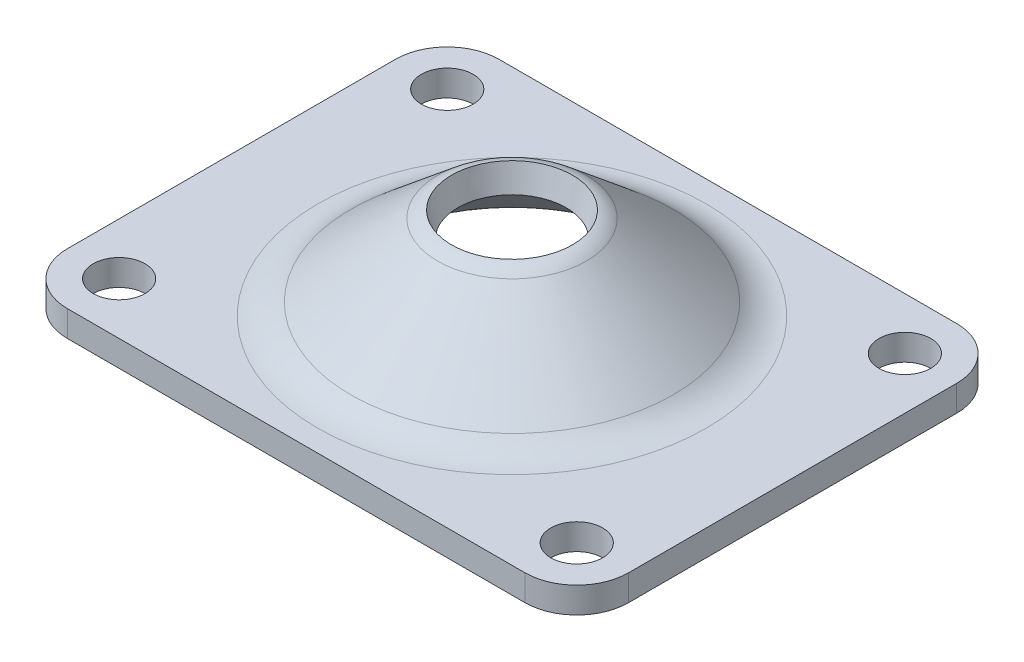
SolidWorks part; units mm, degrees
material "1023 Carbon Steel Sheet (SS)"
ref_plane "Front Plane" through (0, 0, 0) normal (0, 0, 1) x (1, 0, 0)
ref_plane "Top Plane" through (0, 0, 0) normal (0, 1, 0) x (1, 0, 0)
ref_plane "Right Plane" through (0, 0, 0) normal (1, 0, 0) x (0, 0, -1)
sketch "Sketch1" plane through (0, 0, 0) normal (0, 1, 0) x (1, 0, 0)
  line L1 (-26.5, 25) -> (26.5, 25)
  line L2 (-32.5, 19) -> (-32.5, -19)
  line L3 (-26.5, -25) -> (26.5, -25)
  line L4 (32.5, 19) -> (32.5, -19)
  line L5 (0, -25) -> (0, 25) construction
  line L6 (-32.5, 0) -> (32.5, 0) construction
  arc A0 (-32.5, -19) -> (-26.5, -25) centre (-26.5, -19) ccw
  arc A1 (26.5, -25) -> (32.5, -19) centre (26.5, -19) ccw
  arc A2 (26.5, 25) -> (32.5, 19) centre (26.5, 19) cw
  arc A3 (-26.5, 25) -> (-32.5, 19) centre (-26.5, 19) ccw
  circle A4 centre (-26.5, 19) radius 3
  circle A5 centre (26.5, 19) radius 3
  circle A6 centre (26.5, -19) radius 3
  circle A7 centre (-26.5, -19) radius 3
  circle A8 centre (0, 0) radius 22.5
  point P0 (0, 0)
  point P8 (32.5, -25)
  point P11 (32.5, 25)
  point P15 (-32.5, 25)
  dimension "D3" = 6
  dimension "D4" = 6
  dimension "D5" = 45
  dimension "D1" = 50
  dimension "D2" = 65
extrude "Boss-Extrude1" add sketch "Sketch1" along normal blind 3
sketch "Sketch2" plane through (0, 0, 0) normal (0, 0, 1) x (1, 0, 0)
  line L0 (0, 0) -> (0, 13.6376) construction
  line L1 (0, 13.6376) -> (-15.7051, 13.6376) construction
  line L2 (-26.5, 3) -> (26.5, 3) construction
  line L3 (-26.5, 3) -> (26.5, 3) construction
  line L4 (-18.6433, 4.4037) -> (-8.6162, 12.8175)
  line L5 (-16.7149, 2.1056) -> (-6.6878, 10.5193)
  line L6 (-22.5, 3) -> (-22.5, 0)
  line L7 (-7, 13.6376) -> (-6.2838, 10.7244)
  arc A0 (-18.6433, 4.4037) -> (-22.5, 3) centre (-22.5, 9) cw
  arc A1 (-8.6162, 12.8175) -> (-7, 13.6376) centre (-6.045, 9.7533) cw
  arc A2 (-16.7149, 2.1056) -> (-22.5, 0) centre (-22.5, 9) cw
  arc A3 (-6.6878, 10.5193) -> (-6.2838, 10.7244) centre (-6.045, 9.7533) cw
  point P12 (0, 0)
  point P13 (0, 0)
  point P14 (0, 0)
  point P15 (0, 0)
  dimension "D3" = 4
  dimension "D4" = 6
  dimension "D1" = 45
  dimension "D2" = 14
  dimension "D5" = 50
  dimension "D6" = 3
revolve "Revolve3" add sketch "Sketch2" angle 360 about L0
